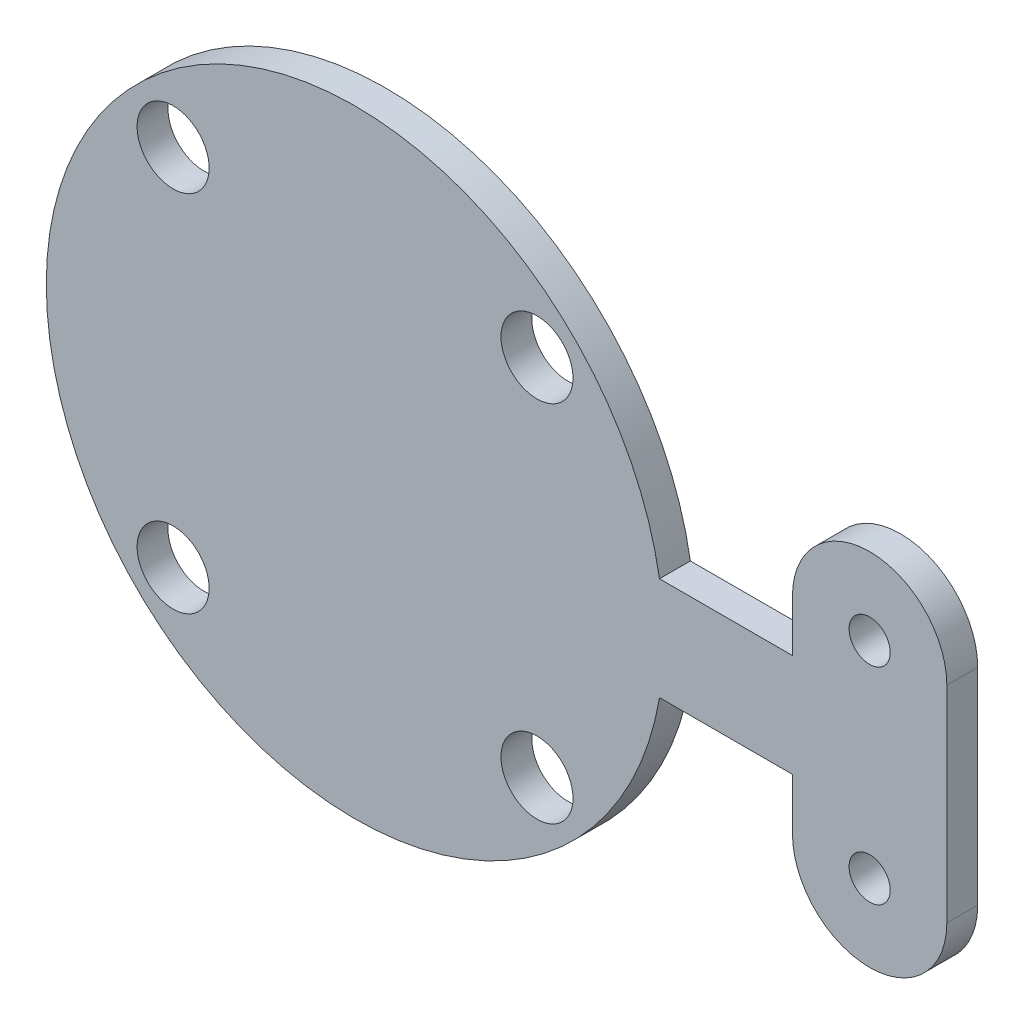
SolidWorks part; units mm, degrees
ref_plane "前视基准面" through (0, 0, 0) normal (0, 0, 1) x (1, 0, 0)
ref_plane "上视基准面" through (0, 0, 0) normal (0, 1, 0) x (1, 0, 0)
ref_plane "右视基准面" through (0, 0, 0) normal (1, 0, 0) x (0, 0, -1)
sketch "草图2" plane through (0, 0, 0) normal (0, 0, 1) x (1, 0, 0)
  circle A0 centre (0, 0) radius 30
  dimension "D1" = 60
extrude "凸台-拉伸1" add sketch "草图2" along normal blind 3 contours A0
sketch "草图3" plane through (0, 0, 3) normal (0, 0, 1) x (1, 0, 0)
  line L2 (0, -1.65) -> (0, 1.65) construction
  line L3 (1.65, 0) -> (-1.65, 0) construction
  circle A0 centre (-17.6777, 17.6777) radius 3.5
  circle A4 centre (17.6777, 17.6777) radius 3.5
  circle A5 centre (17.6777, -17.6777) radius 3.5
  circle A6 centre (-17.6777, -17.6777) radius 3.5
  dimension "D1" = 25
  dimension "D2" = 7
  dimension "D3" = 35.3553
  dimension "D4" = 35.3553
extrude "切除-拉伸1" cut sketch "草图3" against normal blind 3
sketch "草图4" plane through (0, 0, 0) normal (1, 0, 0) x (0, 0, -1)
  line L0 (-3, 30) -> (-3, -30) construction
  line L1 (0, -5) -> (-3, -5)
  line L2 (0, -5) -> (0, 5)
  line L3 (0, 5) -> (-3, 5)
  line L4 (-3, -5) -> (-3, 5)
  line L5 (0, -5) -> (-3, 5) construction
  line L6 (0, 5) -> (-3, -5) construction
  point P0 (-1.5, 0)
  dimension "D1" = 10
  dimension "D2" = 3
extrude "凸台-拉伸2" add sketch "草图4" along normal blind 50
sketch "草图5" plane through (0, 0, 3) normal (0, 0, 1) x (1, 0, 0)
  line L0 (50, 10) -> (50, -10) construction
  line L4 (50, 5) -> (50, -5) construction
  line L5 (57.5, 10) -> (57.5, -10)
  line L6 (42.5, 10) -> (42.5, -10)
  arc A2 (57.5, 10) -> (42.5, 10) centre (50, 10) ccw
  arc A3 (42.5, -10) -> (57.5, -10) centre (50, -10) ccw
  point P4 (50, 0)
  dimension "D2" = 20
  dimension "D1" = 15
  dimension "D3" = 50
extrude "凸台-拉伸3" add sketch "草图5" against normal blind 3
sketch "草图7" plane through (0, 0, 3) normal (0, 0, 1) x (1, 0, 0)
  circle A0 centre (50, 10) radius 2
  circle A1 centre (50, -10) radius 2
  dimension "D1" = 20
  dimension "D2" = 4
  dimension "D3" = 4
extrude "切除-拉伸2" cut sketch "草图7" against normal blind 3
sketch "草图8" plane through (0, 0, 0) normal (0, 0, 1) x (1, 0, 0)
  line L2 (4, 35.5432) -> (4, -35.5432)
  line L4 (-4, 35.5432) -> (-4, -35.5432)
  arc A0 (-4, -35.5432) -> (4, -35.5432) centre (0, -50) ccw
  arc A1 (4, 35.5432) -> (-4, 35.5432) centre (0, 50) ccw
  point P0 (0, 0)
sketch "草图9" plane through (0, 0, 0) normal (0, 0, 1) x (1, 0, 0)
  circle A0 centre (0, 50) radius 7.5
  circle A1 centre (0, -50) radius 7.5
